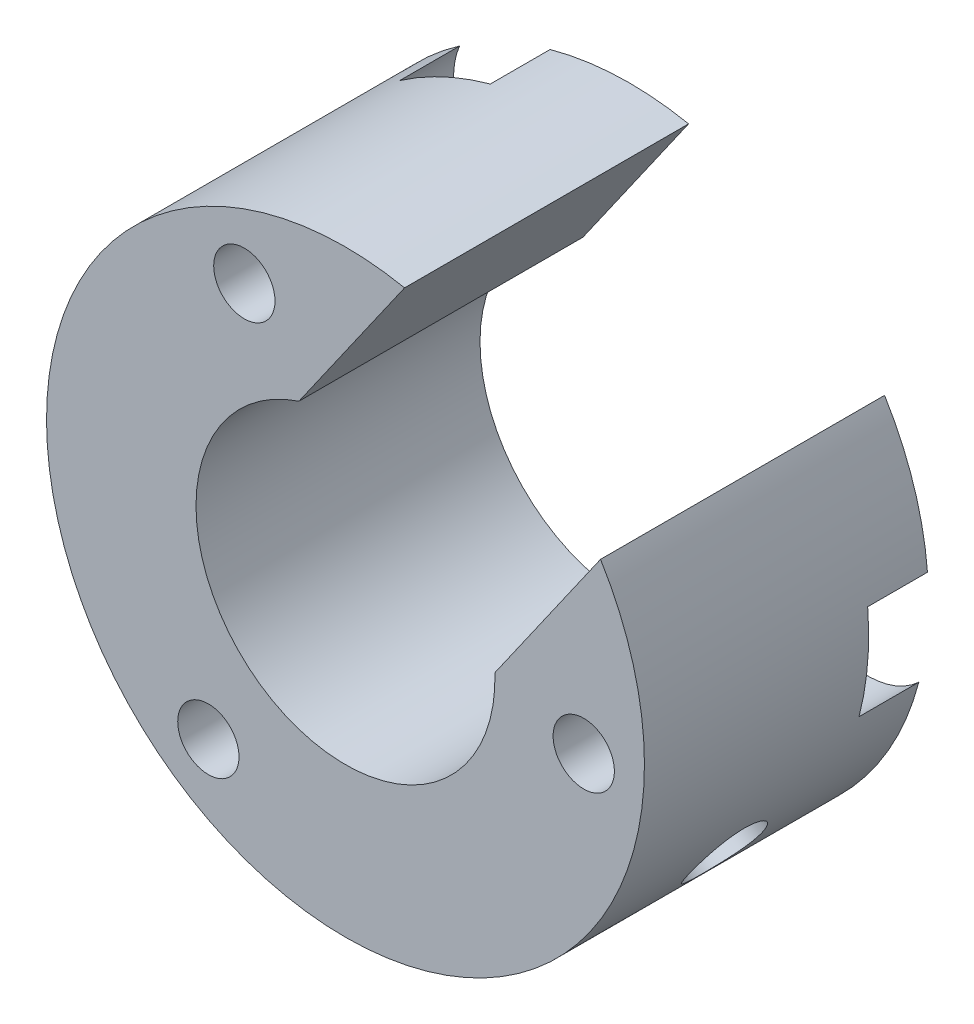
SolidWorks part; units mm, degrees
ref_plane "Front Plane" through (0, 0, 0) normal (0, 0, 1) x (1, 0, 0)
ref_plane "Top Plane" through (0, 0, 0) normal (0, 1, 0) x (1, 0, 0)
ref_plane "Right Plane" through (0, 0, 0) normal (1, 0, 0) x (0, 0, -1)
sketch "Sketch1" plane through (0, 0, 0) normal (0, 0, 1) x (1, 0, 0)
  line L0 (-13.0604, -8.5588) -> (-8.474, -2.0041) construction
  line L2 (-10.0314, 2.7471) -> (-6.4969, 7.7985)
  line L3 (-3.4767, -1.8393) -> (0.0578, 3.212)
  line L5 (-8.474, -2.0041) -> (-3.2195, 5.5053) construction
  line L6 (-6.4969, 7.7985) -> (0.0578, 3.212) construction
  line L7 (-0.5042, -2.6988) -> (-8.474, -2.0041) construction
  line L8 (-8.474, -2.0041) -> (-11.8573, 5.2452) construction
  arc A5 (-10.0314, 2.7471) -> (-3.4767, -1.8393) centre (-8.474, -2.0041) ccw
  arc A6 (-6.4969, 7.7985) -> (0.0578, 3.212) centre (-8.474, -2.0041) ccw
  circle A7 centre (-8.474, -2.0041) radius 8
  circle A8 centre (-13.0604, -8.5588) radius 1.025
  circle A9 centre (-11.8573, 5.2452) radius 1.025
  circle A10 centre (-0.5042, -2.6988) radius 1.025
  dimension "D2" = 8
  dimension "D3" = 16
  dimension "D4" = 2.05
  dimension "D5" = 2.05
  dimension "D8" = 2.05
  dimension "D14" = 10
  dimension "D15" = 20
  dimension "D9" = 60
  dimension "D6" = 8.474
  dimension "D7" = 2.0041
  dimension "D10" = 120
  dimension "D11" = 120
extrude "Boss-Extrude2" add sketch "Sketch1" along normal blind 9.5 contours A10 A7 A8 A9 L2 A6 L3 | A10 A7 L3 A5 L2 A9 A8
sketch "Sketch4" plane through (0, 0, 0) normal (0, 0, -1) x (-1, 0, 0)
  line L0 (2.7409, 6.1893) -> (14.207, -10.1975)
  line L1 (0.2806, -7.7372) -> (16.6674, 3.729)
  line L2 (10.0314, 2.7471) -> (6.4969, 7.7985) construction
  arc A0 (-0.0578, 3.212) -> (6.4969, 7.7985) centre (8.474, -2.0041) ccw construction
  point P7 (8.474, -2.0041)
  point P10 (8.474, -2.0041)
  dimension "D1" = 90
ref_plane "Plane2" through (3.4461, -2.4113, 0) normal (0.8193, -0.5733, 0) x (0, 0, -1)
sketch "Sketch5" plane through (3.4461, -2.4113, 0) normal (0.8193, -0.5733, 0) x (0, 0, -1)
  line L0 (-9.5, 2.6649) -> (-9.5, -16.5002) construction
  line L1 (-9.5, -16.5002) -> (0, -16.5002) construction
  circle A0 centre (-5, -6.5002) radius 1.25
  dimension "D2" = 2.5
  dimension "D1" = 4.5
  dimension "D3" = 10
extrude "Cut-Extrude2" cut sketch "Sketch5" against normal through all both and the other way through all
sketch "Sketch6" plane through (0, 0, 0) normal (0, 0, -1) x (-1, 0, 0)
  circle A0 centre (0.5042, -2.6988) radius 2.5
  circle A1 centre (13.0604, -8.5588) radius 2.5
  circle A2 centre (11.8573, 5.2452) radius 2.5
  dimension "D1" = 5
  dimension "D2" = 5
  dimension "D3" = 5
extrude "Cut-Extrude9" cut sketch "Sketch6" against normal blind 2
sketch "Sketch7" plane through (0, 0, 9.5) normal (0, 0, 1) x (1, 0, 0)
  circle A0 centre (-8.474, -2.0041) radius 8.001
  dimension "D1" = 16.002
